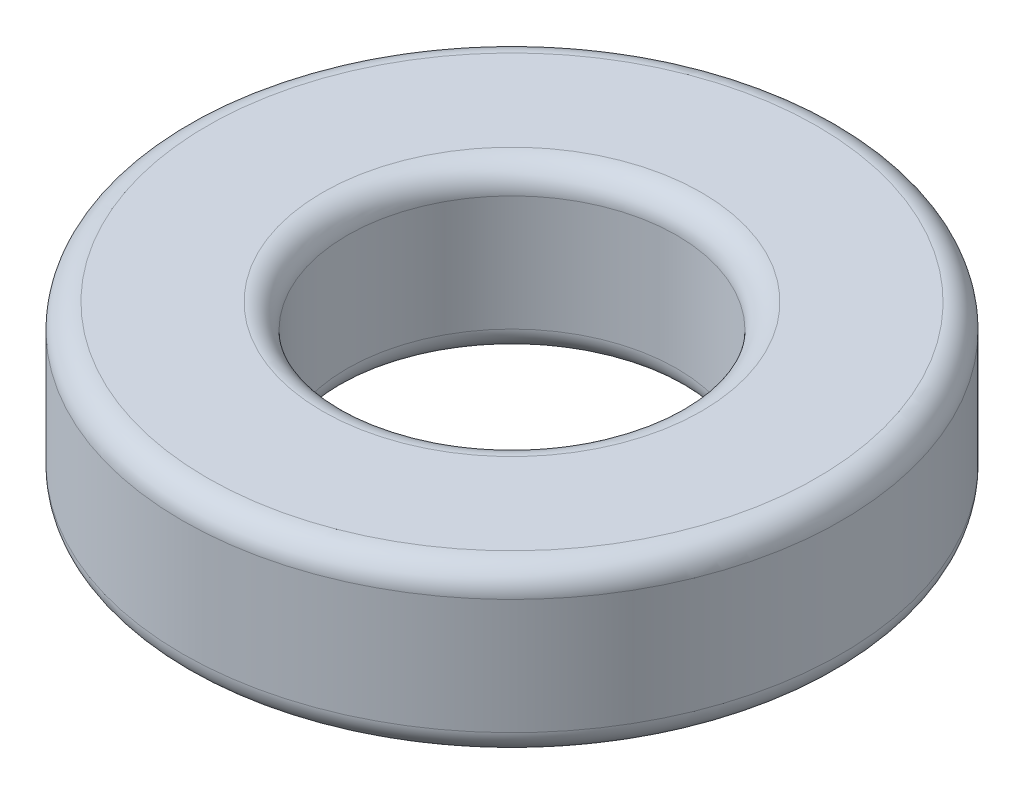
SolidWorks part; units mm, degrees
ref_plane "Front Plane" through (0, 0, 0) normal (0, 0, 1) x (1, 0, 0)
ref_plane "Top Plane" through (0, 0, 0) normal (0, 1, 0) x (1, 0, 0)
ref_plane "Right Plane" through (0, 0, 0) normal (1, 0, 0) x (0, 0, -1)
sketch "Sketch2" plane through (0, 0, 0) normal (0, 1, 0) x (1, 0, 0)
  circle A0 centre (0, 0) radius 50.8
  dimension "D1" = 101.6
sketch "Sketch3" plane through (0, 0, 0) normal (1, 0, 0) x (0, 0, -1)
extrude "Boss-Extrude3" add sketch "Sketch2" along normal mid plane 25.4
sketch "Sketch4" plane through (0, 0, 0) normal (0, 1, 0) x (1, 0, 0)
  circle A0 centre (0, 0) radius 25.4
  circle A2 centre (0, 0) radius 50.8 construction
  dimension "D1" = 25.4
extrude "Cut-Extrude1" cut sketch "Sketch4" against normal mid plane 27.94
fillet "Fillet1" radius 3.81 1 edges at (0, -12.7, 50.8)
fillet "Fillet2" radius 3.81 1 edges at (0, -12.7, 25.4)
fillet "Fillet3" radius 3.81 1 edges at (0, 12.7, 50.8)
fillet "Fillet4" radius 3.81 1 edges at (0, 12.7, 25.4)
